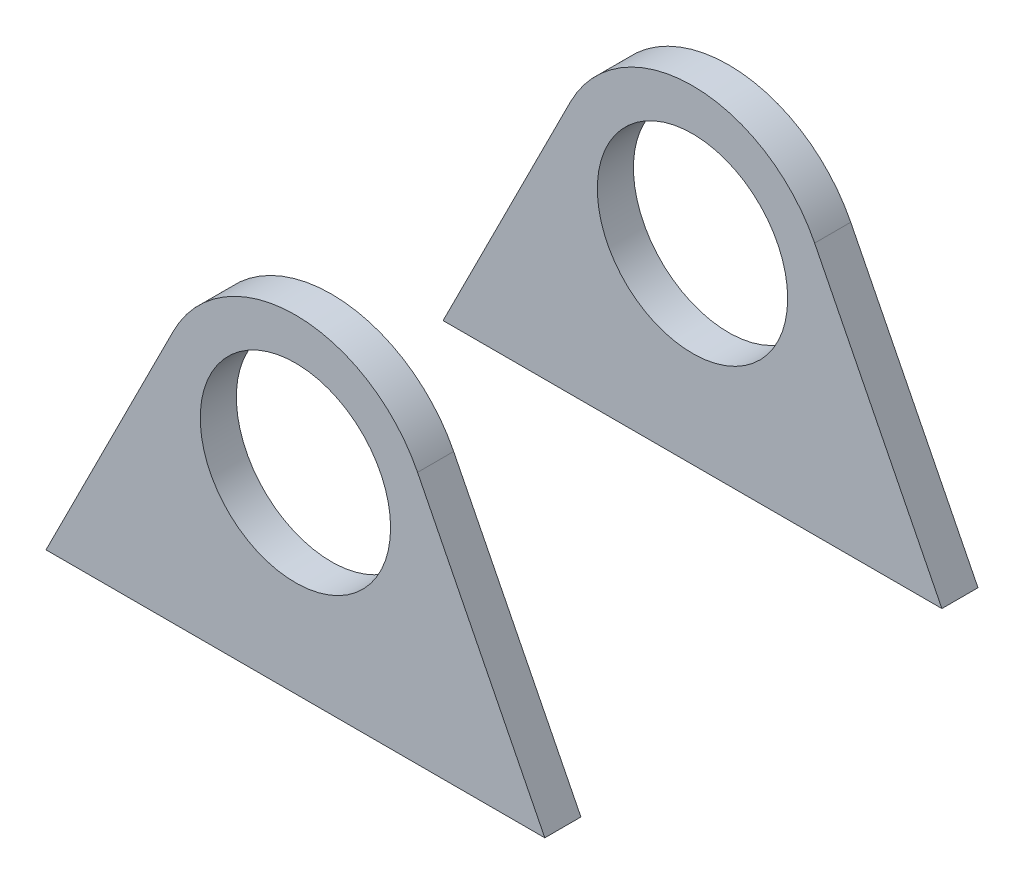
SolidWorks part; units mm, degrees
ref_plane "Front Plane" through (0, 0, 0) normal (0, 0, 1) x (1, 0, 0)
ref_plane "Top Plane" through (0, 0, 0) normal (0, 1, 0) x (1, 0, 0)
ref_plane "Right Plane" through (0, 0, 0) normal (1, 0, 0) x (0, 0, -1)
sketch "Sketch1" plane through (0, 0, 0) normal (0, 0, 1) x (1, 0, 0)
  line L0 (-22.8, -17.5) -> (22.8, -17.5)
  line L1 (-22.8, -17.5) -> (-11.1659, 5.619)
  line L2 (0, -17.5) -> (0, 34.4426) construction
  line L3 (22.8, -17.5) -> (11.1659, 5.619)
  circle A0 centre (0, 0) radius 8.7
  arc A1 (-11.1659, 5.619) -> (11.1659, 5.619) centre (0, 0) cw
  point P6 (0, -17.5)
  point P10 (13.8353, 20.8227)
  point P11 (21.9617, -23.1001)
  point P12 (22.8, 12.4011)
  point P13 (21.9617, -20.552)
  point P14 (21.3659, 12.9807)
  point P15 (16.2982, 18.957)
  point P16 (22.8, -31.1688)
  point P17 (18.2867, 17.0469)
  point P18 (-12.1713, 2.8476)
  point P19 (0, 12.5)
  point P20 (-10.8906, 6.1356)
  point P21 (-10.3786, 6.9666)
  dimension "D1" = 17.4
  dimension "D3" = 30
  dimension "D4" = 12.5
  dimension "D2" = 45.6
extrude "Boss-Extrude1" add sketch "Sketch1" along normal blind 3.3
sketch "Sketch2" plane through (0, 0, 0) normal (0, 1, 0) x (1, 0, 0)
  line L0 (0, -3.3) -> (0, -36.3) construction
  line L1 (-11.1659, -3.3) -> (11.1659, -3.3) construction
  dimension "D1" = 33
ref_point "Point1"
ref_plane "Plane1" through (0, 0, 19.8) normal (0, 0, 1) x (1, 0, 0)
mirror "Mirror6" about plane through (0, 0, 19.8) normal (0, 0, 1) of bodies 101
